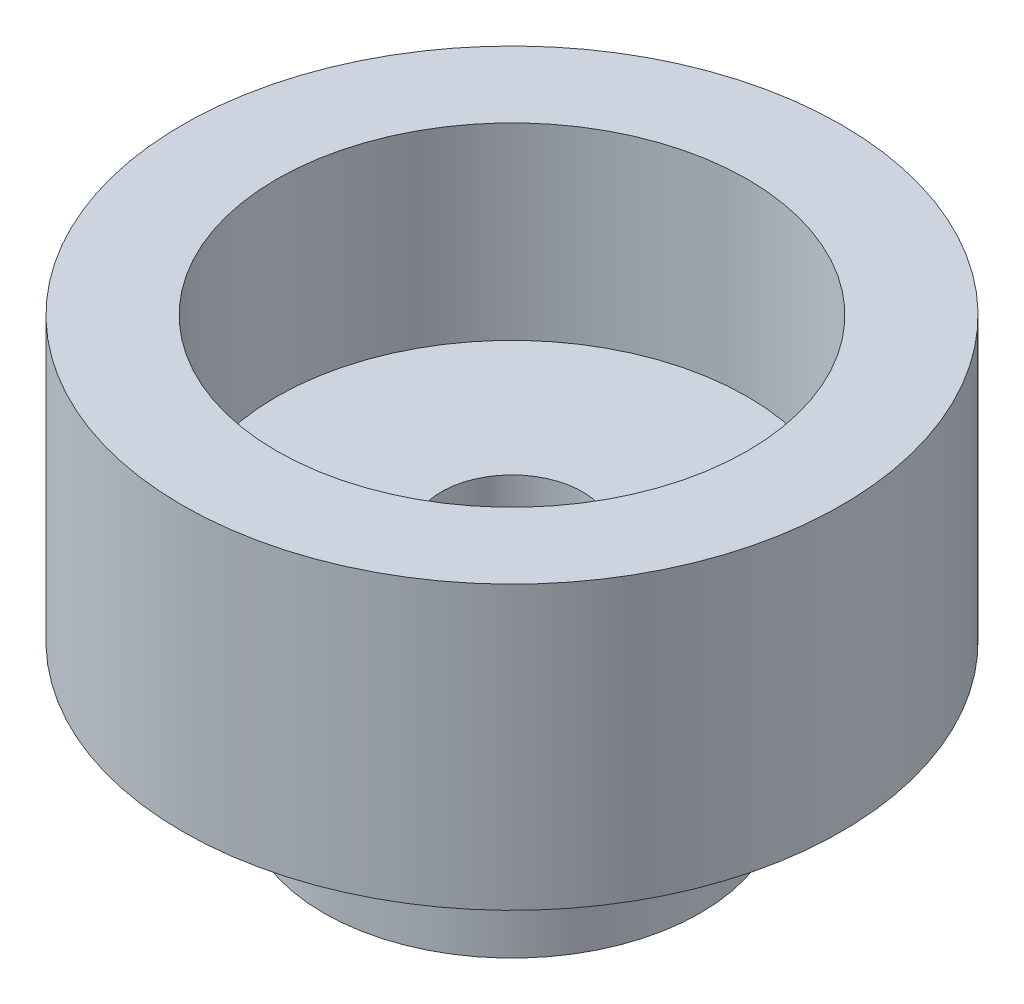
SolidWorks part; units mm, degrees
ref_plane "Front Plane" through (0, 0, 0) normal (0, 0, 1) x (1, 0, 0)
ref_plane "Top Plane" through (0, 0, 0) normal (0, 1, 0) x (1, 0, 0)
ref_plane "Right Plane" through (0, 0, 0) normal (1, 0, 0) x (0, 0, -1)
sketch "Sketch1" plane through (0, 0, 0) normal (0, 1, 0) x (1, 0, 0)
  circle A0 centre (0, 0) radius 0.75
  circle A1 centre (0, 0) radius 1.5
  dimension "D1" = 1.5
  dimension "D2" = 3
extrude "Boss-Extrude1" add sketch "Sketch1" along normal blind 2.5
sketch "Sketch2" plane through (0, 2.5, 0) normal (0, 1, 0) x (1, 0, 0)
  circle A0 centre (0, 0) radius 2.5
  circle A1 centre (0, 0) radius 3.5
  dimension "D1" = 5
  dimension "D2" = 7
extrude "Boss-Extrude2" add sketch "Sketch2" along normal blind 2 separate body
sketch "Sketch3" plane through (0, 2.5, 0) normal (0, -1, 0) x (-1, 0, 0)
  circle A0 centre (0, 0) radius 3.5
  circle A1 centre (0, 0) radius 0.75
extrude "Boss-Extrude3" add sketch "Sketch3" along normal blind 1
sketch "Sketch4" plane through (0, 0, 0) normal (0, -1, 0) x (-1, 0, 0)
  circle A0 centre (0, 0) radius 2
  circle A1 centre (0, 0) radius 0.75
  dimension "D1" = 4
extrude "Boss-Extrude4" add sketch "Sketch4" against normal blind 2
